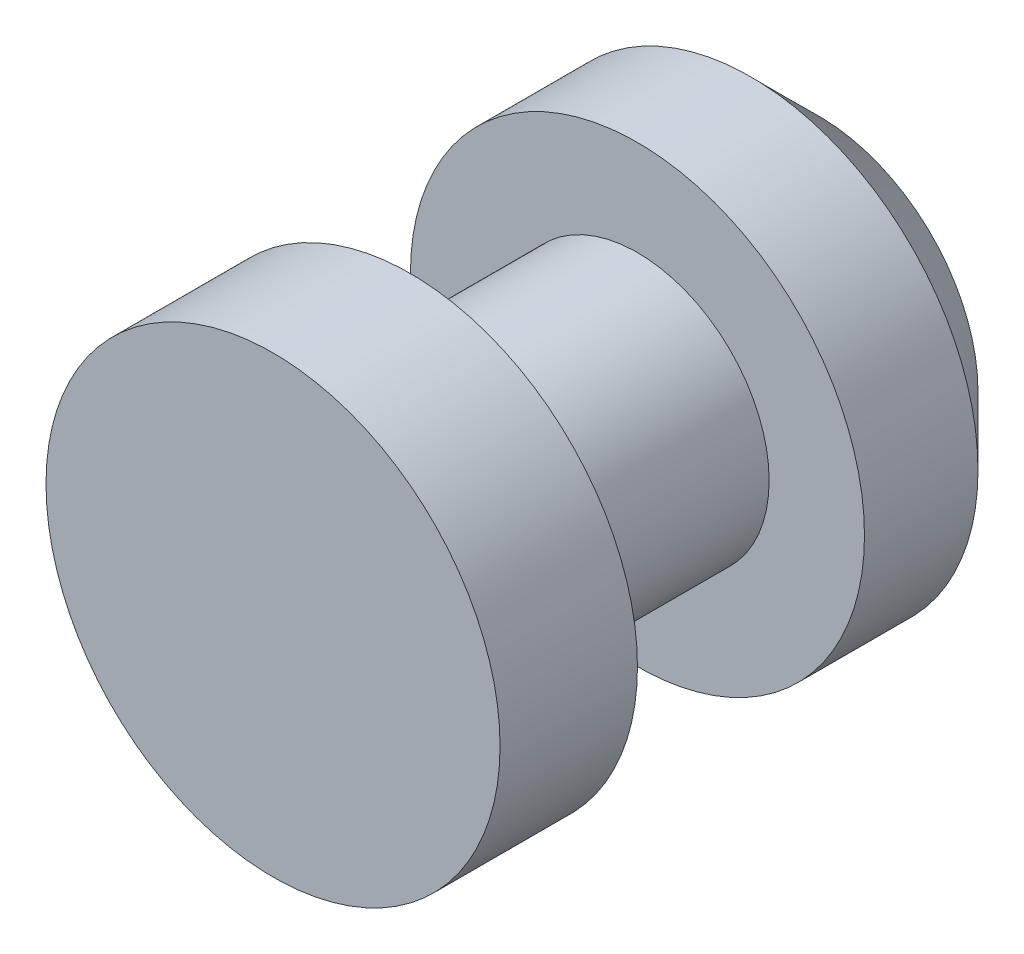
SolidWorks part; units mm, degrees
material "Alloy Steel"
ref_plane "Front Plane" through (0, 0, 0) normal (0, 0, 1) x (1, 0, 0)
ref_plane "Top Plane" through (0, 0, 0) normal (0, 1, 0) x (1, 0, 0)
ref_plane "Right Plane" through (0, 0, 0) normal (1, 0, 0) x (0, 0, -1)
sketch "Sketch1" plane through (0, 0, 0) normal (0, 1, 0) x (1, 0, 0)
  line L0 (0, -0.5526) -> (0, 0.65)
  line L1 (-0.5, -0.25) -> (-0.5, -0.5526)
  line L2 (-0.29, 0.25) -> (-0.5, 0.25)
  line L3 (-0.5, 0.25) -> (-0.5, 0.5)
  line L4 (-0.35, 0.65) -> (0, 0.65)
  line L5 (-0.29, 0.25) -> (-0.29, -0.25)
  line L6 (-0.5, -0.5526) -> (0, -0.5526)
  line L8 (-0.29, 0) -> (0, 0) construction
  line L9 (-0.5, 0.5) -> (-0.35, 0.65)
  line L10 (-0.29, -0.25) -> (-0.5, -0.25)
  point P7 (-0.5, 0.65)
  point P15 (-0.395, -0.25)
  dimension "D2" = 0.4
  dimension "D3" = 0.29
  dimension "D4" = 0.25
  dimension "D5" = 0.3026
  dimension "D8" = 0.5
revolve "Revolve1" add sketch "Sketch1" angle 360 about L0
